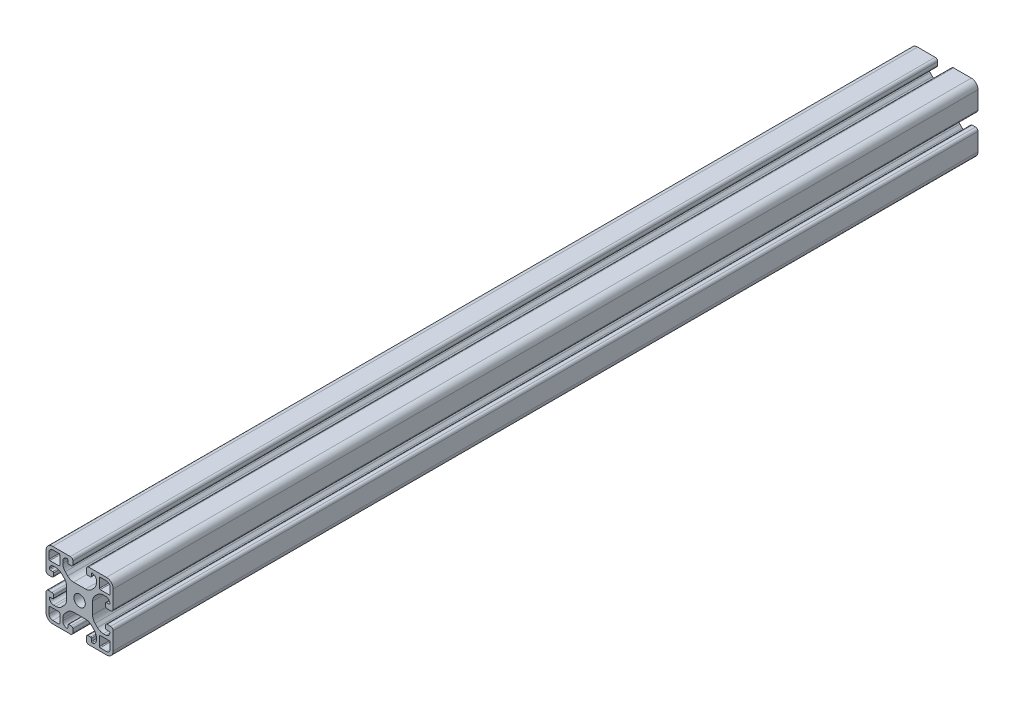
SolidWorks part; units mm, degrees
ref_plane "Plan de face" through (0, 0, 0) normal (0, 0, 1) x (1, 0, 0)
ref_plane "Plan de dessus" through (0, 0, 0) normal (0, 1, 0) x (1, 0, 0)
ref_plane "Plan de droite" through (0, 0, 0) normal (1, 0, 0) x (0, 0, -1)
ref_plane "Plan1" through (0, 0, -30) normal (0, 0, -1) x (-1, 0, 0)
sketch "Esquisse1" plane through (0, 0, -30) normal (0, 0, -1) x (-1, 0, 0)
  line L0 (-4.5, 15) -> (-4.5, 13.5)
  line L1 (-4, 13) -> (-2.5, 13)
  line L2 (-4.5, 10) -> (-5.8076, 10)
  line L3 (-9.3431, 11.4645) -> (-10.7855, 12.9069)
  line L4 (-12.25, 16.4424) -> (-12.25, 23.5576)
  line L5 (-10.7855, 27.0931) -> (-9.3431, 28.5355)
  line L6 (-5.8076, 30) -> (-4.5, 30)
  line L7 (-2.5, 27) -> (-4, 27)
  line L8 (-4.5, 26.5) -> (-4.5, 25)
  line L9 (-3.5, 24) -> (-1.5, 24)
  line L10 (0, 25.5) -> (0, 36)
  line L11 (-4, 40) -> (-14.5, 40)
  line L12 (-16, 38.5) -> (-16, 36.5)
  line L13 (-15, 35.5) -> (-13.5, 35.5)
  line L14 (-13, 36) -> (-13, 37.5)
  line L15 (-10, 35.5) -> (-10, 34.1924)
  line L16 (-11.4645, 30.6569) -> (-12.9069, 29.2145)
  line L17 (-16.4424, 27.75) -> (-23.5576, 27.75)
  line L18 (-27.0931, 29.2145) -> (-28.5355, 30.6569)
  line L19 (-30, 34.1924) -> (-30, 35.5)
  line L20 (-27, 37.5) -> (-27, 36)
  line L21 (-26.5, 35.5) -> (-25, 35.5)
  line L22 (-24, 36.5) -> (-24, 38.5)
  line L23 (-25.5, 40) -> (-36, 40)
  line L24 (-40, 36) -> (-40, 25.5)
  line L25 (-38.5, 24) -> (-36.5, 24)
  line L26 (-35.5, 25) -> (-35.5, 26.5)
  line L27 (-36, 27) -> (-37.5, 27)
  line L28 (-35.5, 30) -> (-34.1924, 30)
  line L29 (-30.6569, 28.5355) -> (-29.2145, 27.0931)
  line L30 (-27.75, 23.5576) -> (-27.75, 16.4424)
  line L31 (-29.2145, 12.9069) -> (-30.6569, 11.4645)
  line L32 (-34.1924, 10) -> (-35.5, 10)
  line L33 (-37.5, 13) -> (-36, 13)
  line L34 (-35.5, 13.5) -> (-35.5, 15)
  line L35 (-36.5, 16) -> (-38.5, 16)
  line L36 (-40, 14.5) -> (-40, 4)
  line L37 (-36, 0) -> (-25.5, 0)
  line L38 (-24, 1.5) -> (-24, 3.5)
  line L39 (-25, 4.5) -> (-26.5, 4.5)
  line L40 (-27, 4) -> (-27, 2.5)
  line L41 (-30, 4.5) -> (-30, 5.8076)
  line L42 (-28.5355, 9.3431) -> (-27.0931, 10.7855)
  line L43 (-23.5576, 12.25) -> (-16.4424, 12.25)
  line L44 (-12.9069, 10.7855) -> (-11.4645, 9.3431)
  line L45 (-10, 5.8076) -> (-10, 4.5)
  line L46 (-13, 2.5) -> (-13, 4)
  line L47 (-13.5, 4.5) -> (-15, 4.5)
  line L48 (-16, 3.5) -> (-16, 1.5)
  line L49 (-14.5, 0) -> (-4, 0)
  line L50 (0, 4) -> (0, 14.5)
  line L51 (-1.5, 16) -> (-3.5, 16)
  line L52 (-4, 1.8) -> (-7.7, 1.8)
  line L53 (-8.2, 2.3) -> (-8.2, 7.7)
  line L54 (-7.7, 8.2) -> (-2.3, 8.2)
  line L55 (-1.8, 7.7) -> (-1.8, 4)
  line L56 (-38.2, 4) -> (-38.2, 7.7)
  line L57 (-37.7, 8.2) -> (-32.3, 8.2)
  line L58 (-31.8, 7.7) -> (-31.8, 2.3)
  line L59 (-32.3, 1.8) -> (-36, 1.8)
  line L60 (-36, 38.2) -> (-32.3, 38.2)
  line L61 (-31.8, 37.7) -> (-31.8, 32.3)
  line L62 (-32.3, 31.8) -> (-37.7, 31.8)
  line L63 (-38.2, 32.3) -> (-38.2, 36)
  line L64 (-1.8, 36) -> (-1.8, 32.3)
  line L65 (-2.3, 31.8) -> (-7.7, 31.8)
  line L66 (-8.2, 32.3) -> (-8.2, 37.7)
  line L67 (-7.7, 38.2) -> (-4, 38.2)
  arc A0 (-4.5, 13.5) -> (-4, 13) centre (-4, 13.5) ccw
  arc A1 (-2.5, 13) -> (-2, 12.5) centre (-2.5, 12.5) cw
  arc A2 (-2, 12.5) -> (-4.5, 10) centre (-4.5, 12.5) cw
  arc A3 (-5.8076, 10) -> (-9.3431, 11.4645) centre (-5.8076, 15) cw
  arc A4 (-10.7855, 12.9069) -> (-12.25, 16.4424) centre (-7.25, 16.4424) cw
  arc A5 (-12.25, 23.5576) -> (-10.7855, 27.0931) centre (-7.25, 23.5576) cw
  arc A6 (-9.3431, 28.5355) -> (-5.8076, 30) centre (-5.8076, 25) cw
  arc A7 (-4.5, 30) -> (-2, 27.5) centre (-4.5, 27.5) cw
  arc A8 (-2, 27.5) -> (-2.5, 27) centre (-2.5, 27.5) cw
  arc A9 (-4, 27) -> (-4.5, 26.5) centre (-4, 26.5) ccw
  arc A10 (-4.5, 25) -> (-3.5, 24) centre (-3.5, 25) ccw
  arc A11 (-1.5, 24) -> (0, 25.5) centre (-1.5, 25.5) ccw
  arc A12 (0, 36) -> (-4, 40) centre (-4, 36) ccw
  arc A13 (-14.5, 40) -> (-16, 38.5) centre (-14.5, 38.5) ccw
  arc A14 (-16, 36.5) -> (-15, 35.5) centre (-15, 36.5) ccw
  arc A15 (-13.5, 35.5) -> (-13, 36) centre (-13.5, 36) ccw
  arc A16 (-13, 37.5) -> (-12.5, 38) centre (-12.5, 37.5) cw
  arc A17 (-12.5, 38) -> (-10, 35.5) centre (-12.5, 35.5) cw
  arc A18 (-10, 34.1924) -> (-11.4645, 30.6569) centre (-15, 34.1924) cw
  arc A19 (-12.9069, 29.2145) -> (-16.4424, 27.75) centre (-16.4424, 32.75) cw
  arc A20 (-23.5576, 27.75) -> (-27.0931, 29.2145) centre (-23.5576, 32.75) cw
  arc A21 (-28.5355, 30.6569) -> (-30, 34.1924) centre (-25, 34.1924) cw
  arc A22 (-30, 35.5) -> (-27.5, 38) centre (-27.5, 35.5) cw
  arc A23 (-27.5, 38) -> (-27, 37.5) centre (-27.5, 37.5) cw
  arc A24 (-27, 36) -> (-26.5, 35.5) centre (-26.5, 36) ccw
  arc A25 (-25, 35.5) -> (-24, 36.5) centre (-25, 36.5) ccw
  arc A26 (-24, 38.5) -> (-25.5, 40) centre (-25.5, 38.5) ccw
  arc A27 (-36, 40) -> (-40, 36) centre (-36, 36) ccw
  arc A28 (-40, 25.5) -> (-38.5, 24) centre (-38.5, 25.5) ccw
  arc A29 (-36.5, 24) -> (-35.5, 25) centre (-36.5, 25) ccw
  arc A30 (-35.5, 26.5) -> (-36, 27) centre (-36, 26.5) ccw
  arc A31 (-37.5, 27) -> (-38, 27.5) centre (-37.5, 27.5) cw
  arc A32 (-38, 27.5) -> (-35.5, 30) centre (-35.5, 27.5) cw
  arc A33 (-34.1924, 30) -> (-30.6569, 28.5355) centre (-34.1924, 25) cw
  arc A34 (-29.2145, 27.0931) -> (-27.75, 23.5576) centre (-32.75, 23.5576) cw
  arc A35 (-27.75, 16.4424) -> (-29.2145, 12.9069) centre (-32.75, 16.4424) cw
  arc A36 (-30.6569, 11.4645) -> (-34.1924, 10) centre (-34.1924, 15) cw
  arc A37 (-35.5, 10) -> (-38, 12.5) centre (-35.5, 12.5) cw
  arc A38 (-38, 12.5) -> (-37.5, 13) centre (-37.5, 12.5) cw
  arc A39 (-36, 13) -> (-35.5, 13.5) centre (-36, 13.5) ccw
  arc A40 (-35.5, 15) -> (-36.5, 16) centre (-36.5, 15) ccw
  arc A41 (-38.5, 16) -> (-40, 14.5) centre (-38.5, 14.5) ccw
  arc A42 (-40, 4) -> (-36, 0) centre (-36, 4) ccw
  arc A43 (-25.5, 0) -> (-24, 1.5) centre (-25.5, 1.5) ccw
  arc A44 (-24, 3.5) -> (-25, 4.5) centre (-25, 3.5) ccw
  arc A45 (-26.5, 4.5) -> (-27, 4) centre (-26.5, 4) ccw
  arc A46 (-27, 2.5) -> (-27.5, 2) centre (-27.5, 2.5) cw
  arc A47 (-27.5, 2) -> (-30, 4.5) centre (-27.5, 4.5) cw
  arc A48 (-30, 5.8076) -> (-28.5355, 9.3431) centre (-25, 5.8076) cw
  arc A49 (-27.0931, 10.7855) -> (-23.5576, 12.25) centre (-23.5576, 7.25) cw
  arc A50 (-16.4424, 12.25) -> (-12.9069, 10.7855) centre (-16.4424, 7.25) cw
  arc A51 (-11.4645, 9.3431) -> (-10, 5.8076) centre (-15, 5.8076) cw
  arc A52 (-10, 4.5) -> (-12.5, 2) centre (-12.5, 4.5) cw
  arc A53 (-12.5, 2) -> (-13, 2.5) centre (-12.5, 2.5) cw
  arc A54 (-13, 4) -> (-13.5, 4.5) centre (-13.5, 4) ccw
  arc A55 (-15, 4.5) -> (-16, 3.5) centre (-15, 3.5) ccw
  arc A56 (-16, 1.5) -> (-14.5, 0) centre (-14.5, 1.5) ccw
  arc A57 (-4, 0) -> (0, 4) centre (-4, 4) ccw
  arc A58 (0, 14.5) -> (-1.5, 16) centre (-1.5, 14.5) ccw
  arc A59 (-3.5, 16) -> (-4.5, 15) centre (-3.5, 15) ccw
  circle A60 centre (-20, 20) radius 3.4
  arc A61 (-1.8, 4) -> (-4, 1.8) centre (-4, 4) cw
  arc A62 (-7.7, 1.8) -> (-8.2, 2.3) centre (-7.7, 2.3) cw
  arc A63 (-8.2, 7.7) -> (-7.7, 8.2) centre (-7.7, 7.7) cw
  arc A64 (-2.3, 8.2) -> (-1.8, 7.7) centre (-2.3, 7.7) cw
  arc A65 (-36, 1.8) -> (-38.2, 4) centre (-36, 4) cw
  arc A66 (-38.2, 7.7) -> (-37.7, 8.2) centre (-37.7, 7.7) cw
  arc A67 (-32.3, 8.2) -> (-31.8, 7.7) centre (-32.3, 7.7) cw
  arc A68 (-31.8, 2.3) -> (-32.3, 1.8) centre (-32.3, 2.3) cw
  arc A69 (-38.2, 36) -> (-36, 38.2) centre (-36, 36) cw
  arc A70 (-32.3, 38.2) -> (-31.8, 37.7) centre (-32.3, 37.7) cw
  arc A71 (-31.8, 32.3) -> (-32.3, 31.8) centre (-32.3, 32.3) cw
  arc A72 (-37.7, 31.8) -> (-38.2, 32.3) centre (-37.7, 32.3) cw
  arc A73 (-4, 38.2) -> (-1.8, 36) centre (-4, 36) cw
  arc A74 (-1.8, 32.3) -> (-2.3, 31.8) centre (-2.3, 32.3) cw
  arc A75 (-7.7, 31.8) -> (-8.2, 32.3) centre (-7.7, 32.3) cw
  arc A76 (-8.2, 37.7) -> (-7.7, 38.2) centre (-7.7, 37.7) cw
extrude "Boss.-Extru.1" add sketch "Esquisse1" against normal blind 515
